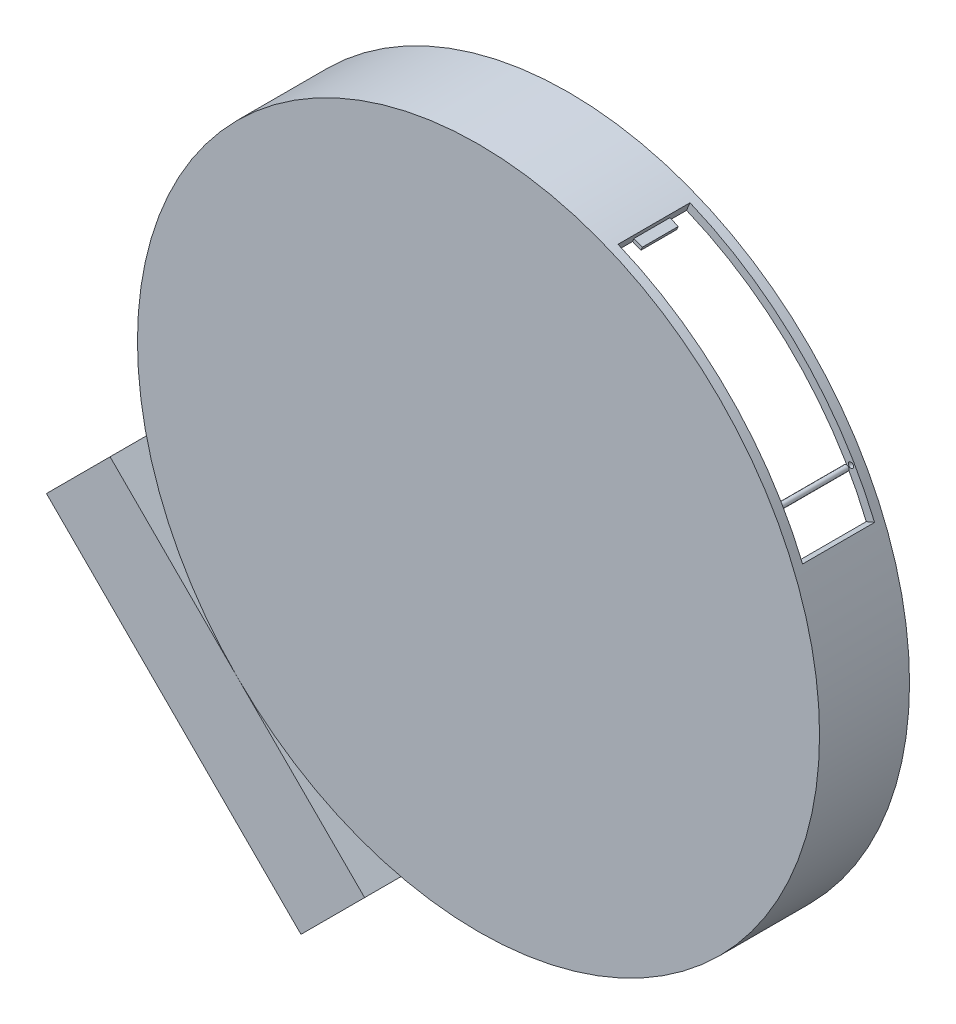
SolidWorks part; units mm, degrees
material "Plastique personnalisé"
ref_plane "Plan de face" through (0, 0, 0) normal (0, 0, 1) x (1, 0, 0)
ref_plane "Plan de dessus" through (0, 0, 0) normal (0, 1, 0) x (1, 0, 0)
ref_plane "Plan de droite" through (0, 0, 0) normal (1, 0, 0) x (0, 0, -1)
sketch "Esquisse1" plane through (0, 0, 0) normal (0, 0, 1) x (1, 0, 0)
  line L20 (0, 0) -> (-267.9935, -267.9935)
  line L21 (-267.9935, -267.9935) -> (-126.5721, -409.4148)
  line L22 (-126.5721, -409.4148) -> (-197.2828, -480.1255)
  line L23 (-197.2828, -480.1255) -> (-480.1255, -197.2828)
  line L26 (-267.9935, -267.9935) -> (-409.4148, -126.5721)
  line L27 (-409.4148, -126.5721) -> (-480.1255, -197.2828)
  circle A0 centre (0, 0) radius 379
  dimension "D1" = 758
  dimension "D5" = 100
  dimension "D6" = 200
  dimension "D7" = 200
  dimension "D8" = 400
  dimension "D9" = 100
extrude "Boss.-Extru.1" add sketch "Esquisse1" along normal blind 100
shell "Coque3" thickness 10
sketch "Esquisse3" plane through (0, 0, 90) normal (0, 0, -1) x (-1, 0, 0)
  line L1 (-350.1503, 145.037) -> (0, 0)
  line L2 (0, 0) -> (-145.037, 350.1503)
  circle A0 centre (0, 0) radius 379 construction
  arc A1 (-267.9935, 267.9935) -> (-145.037, 350.1503) centre (0, 0) cw
  arc A2 (-267.9935, 267.9935) -> (-350.1503, 145.037) centre (0, 0) ccw
  dimension "D1" = 22.5
  dimension "D2" = 22.5
extrude "Enlèv. mat.-Extru.4" cut sketch "Esquisse3" along normal blind 80
sketch "Esquisse5" plane through (0, 0, 90) normal (0, 0, -1) x (-1, 0, 0)
  line L0 (0, 0) -> (-267.9935, 267.9935)
  arc A0 (-145.037, 350.1503) -> (-350.1503, 145.037) centre (0, 0) ccw construction
  circle A1 centre (-323.8935, 187) radius 3
  arc A2 (-323.8935, 187) -> (-264.4579, 264.4579) centre (0, 0) cw
  dimension "D2" = 6
extrude "Boss.-Extru.3" add sketch "Esquisse5" along normal blind 85 and the other way blind 5 contours A1
sketch "Esquisse7" plane through (0, 0, 0) normal (0, 0, -1) x (-1, 0, 0)
  arc A0 (-267.9935, 267.9935) -> (-328.2236, 189.5) centre (0, 0) ccw
  circle A1 centre (0, 0) radius 379 construction
  circle A3 centre (-323.8935, 187) radius 3
  dimension "D1" = 6
  dimension "D2" = 15
extrude "Enlèv. mat.-Extru.12" cut sketch "Esquisse7" against normal blind 15 contours A3
sketch "Esquisse12" plane through (0, 0, 0) normal (0.9239, -0.3827, 0) x (0, 0, -1)
  line L0 (-10, 369) -> (-90, 369) construction
  line L1 (-70, 369) -> (-30, 369)
  line L2 (-70, 369) -> (-70, 373)
  line L3 (-70, 373) -> (-30, 373)
  line L4 (-30, 369) -> (-30, 373)
  line L5 (-90, 369) -> (-50, 369)
  line M4 (-90, 369) -> (-10, 369)
  dimension "D1" = 40
  dimension "D2" = 40
  dimension "D4" = 4
extrude "Boss.-Extru.27" add sketch "Esquisse12" along normal blind 10 contours L1 L4 L3 L2 M4
